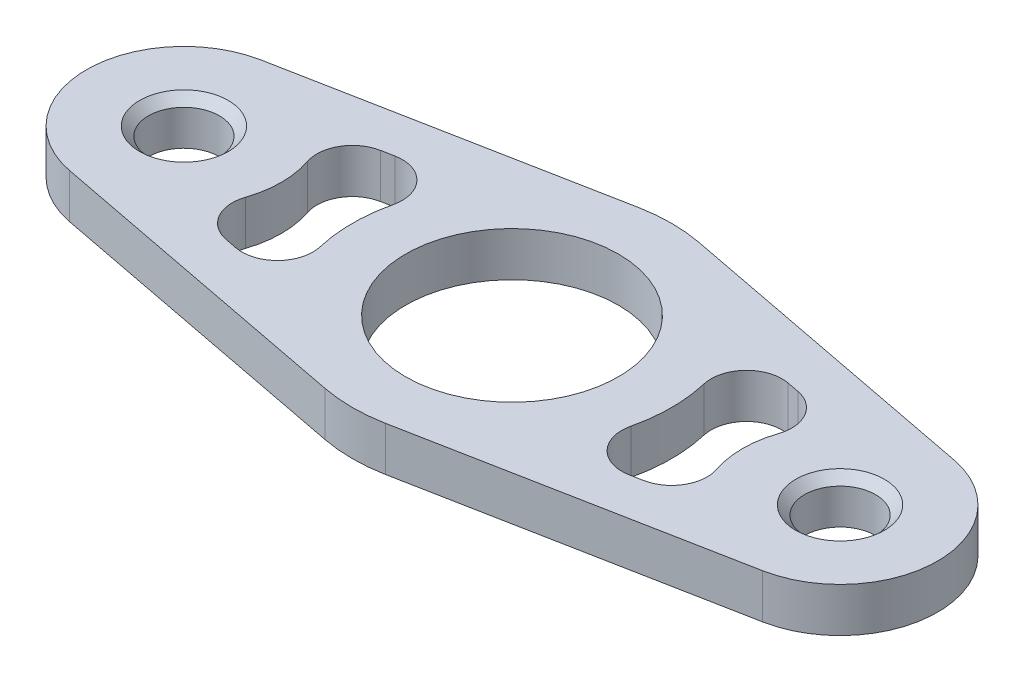
SolidWorks part; units mm, degrees
ref_plane "Front Plane" through (0, 0, 0) normal (0, 0, 1) x (1, 0, 0)
ref_plane "Top Plane" through (0, 0, 0) normal (0, 1, 0) x (1, 0, 0)
ref_plane "Right Plane" through (0, 0, 0) normal (1, 0, 0) x (0, 0, -1)
sketch "Sketch1" plane through (0, 0, 0) normal (0, 1, 0) x (1, 0, 0)
  line L0 (0, 28.1578) -> (0, 0) construction
  line L1 (37, 0) -> (-37, 0) construction
  line L2 (-39.0811, 10.8013) -> (-3.4054, 17.6749)
  line L3 (-29.0821, 7.6359) -> (-14.6845, 10.4098)
  line L4 (-29.0821, -7.6359) -> (-14.6845, -10.4098)
  line L5 (-39.0811, -10.8013) -> (-3.4054, -17.6749)
  line L6 (-38.1351, 5.8916) -> (-2.4595, 12.7652) construction
  line L7 (39.0811, -10.8013) -> (3.4054, -17.6749)
  line L8 (29.0821, -7.6359) -> (14.6845, -10.4098)
  line L9 (29.0821, 7.6359) -> (14.6845, 10.4098)
  line L10 (39.0811, 10.8013) -> (3.4054, 17.6749)
  arc A0 (-14.6845, 10.4098) -> (-14.6845, -10.4098) centre (0, 0) ccw
  circle A1 centre (0, 0) radius 12
  arc A2 (-39.0811, 10.8013) -> (-39.0811, -10.8013) centre (-37, 0) ccw
  circle A3 centre (-37, 0) radius 4
  arc A4 (-3.4054, -17.6749) -> (3.4054, -17.6749) centre (0, 0) ccw
  arc A5 (-29.0821, -7.6359) -> (-29.0821, 7.6359) centre (-37, 0) ccw
  arc A6 (29.0821, -7.6359) -> (29.0821, 7.6359) centre (37, 0) cw
  circle A7 centre (37, 0) radius 4
  arc A8 (39.0811, 10.8013) -> (39.0811, -10.8013) centre (37, 0) cw
  arc A9 (14.6845, 10.4098) -> (14.6845, -10.4098) centre (0, 0) cw
  arc A10 (3.4054, 17.6749) -> (-3.4054, 17.6749) centre (0, 0) ccw
  arc A11 (14.6845, -10.4098) -> (14.6845, 10.4098) centre (0, 0) ccw
  dimension "D1" = 36
  dimension "D2" = 24
  dimension "D3" = 22
  dimension "D4" = 8
  dimension "D5" = 37
  dimension "D7" = 5
  dimension "D6" = 5
extrude "Boss-Extrude1" add sketch "Sketch1" along normal mid plane 5 contours L10 A10 L2 A2 L5 A4 L7 A8 A7 A3 A1 L4 A5 L3 A0 A9 L9 A6 L8
fillet "Fillet1" radius 4 8 edges at (14.6845, 0, 10.4098) (29.0821, 0, 7.6359) (29.0821, 0, -7.6359) (14.6845, 0, -10.4098) (-14.6845, 0, 10.4098) (-14.6845, 0, -10.4098) (-29.0821, 0, 7.6359) (-29.0821, 0, -7.6359)
chamfer "Chamfer1" distance 1 angle 45 2 edges at (37, 2.5, 4) (-37, 2.5, 4)
